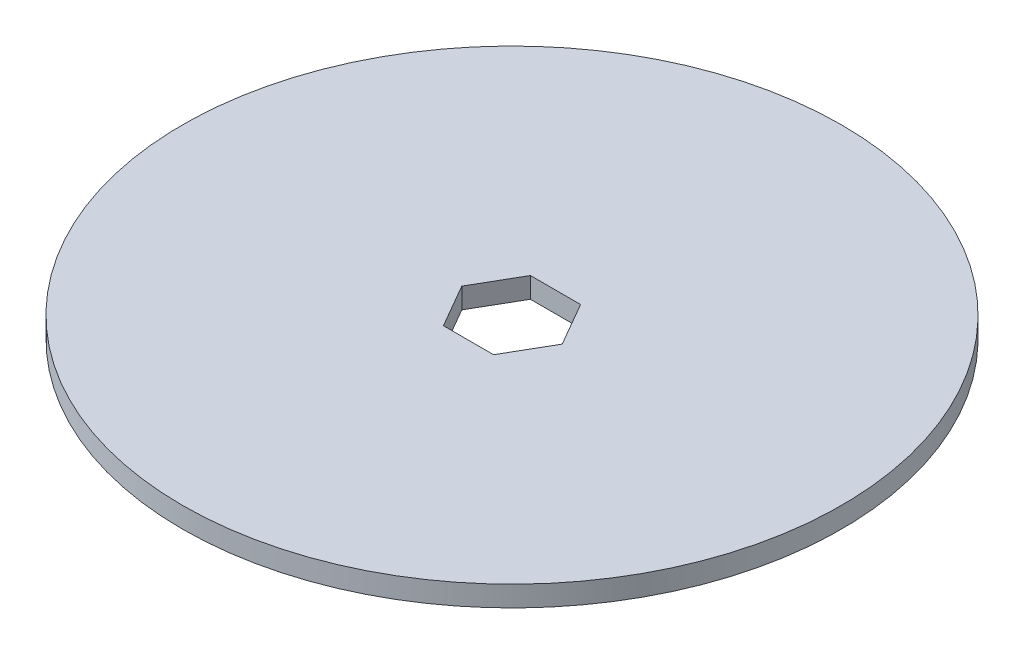
SolidWorks part; units mm, degrees
material "6061-T6 (SS)"
ref_plane "Front Plane" through (0, 0, 0) normal (0, 0, 1) x (1, 0, 0)
ref_plane "Top Plane" through (0, 0, 0) normal (0, 1, 0) x (1, 0, 0)
ref_plane "Right Plane" through (0, 0, 0) normal (1, 0, 0) x (0, 0, -1)
sketch "Sketch2" plane through (0, 0, 0) normal (0, 1, 0) x (1, 0, 0)
  line L43 (3.87, 0) -> (1.935, 3.3515)
  line L44 (1.935, 3.3515) -> (-1.935, 3.3515)
  line L45 (-1.935, 3.3515) -> (-3.87, 0)
  line L46 (-3.87, 0) -> (-1.935, -3.3515)
  line L47 (-1.935, -3.3515) -> (1.935, -3.3515)
  line L48 (1.935, -3.3515) -> (3.87, 0)
  circle A28 centre (0, 0) radius 3.3515 construction
  circle A29 centre (0, 0) radius 25.4
  point P23 (0, 0)
  point P52 (0, 0)
  point P95 (0, 0)
  dimension "D1" = 50.8
  dimension "D5" = 3.87
extrude "Boss-Extrude2" add sketch "Sketch2" along normal blind 1.5875 contours A29 L48 L47 L46 L45 L44 L43
